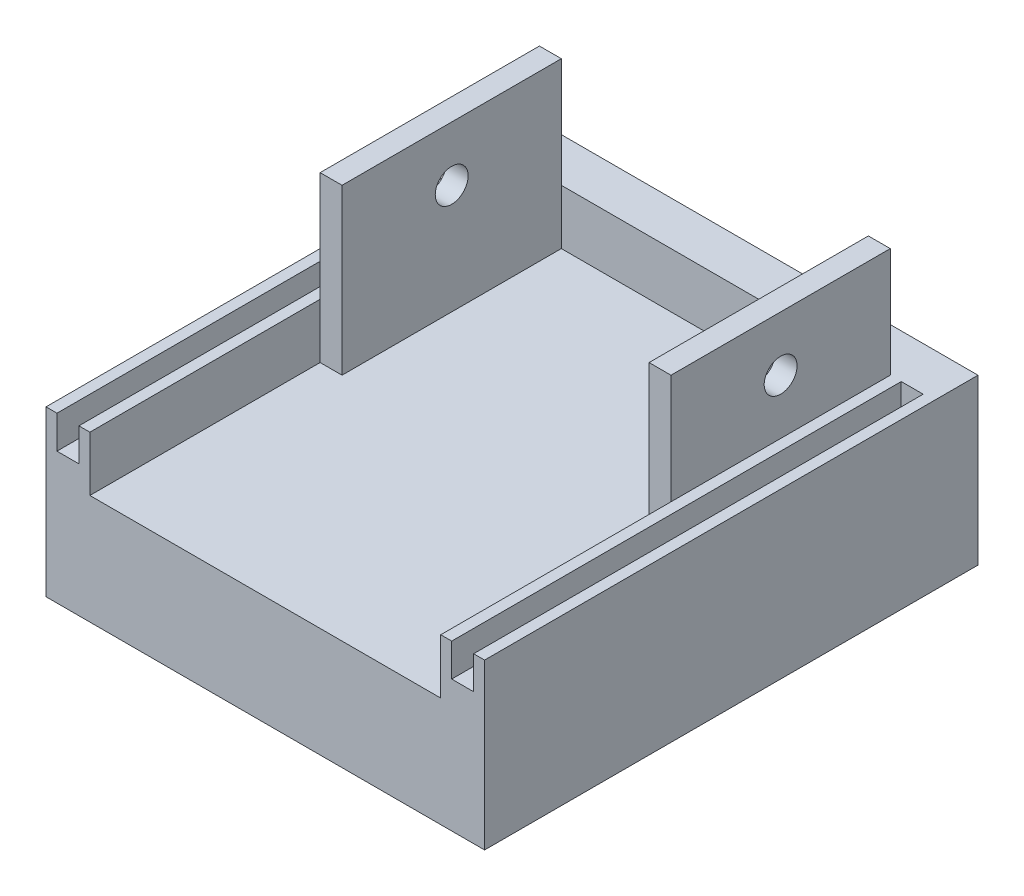
SolidWorks part; units mm, degrees
ref_plane "Front Plane" through (0, 0, 0) normal (0, 0, 1) x (1, 0, 0)
ref_plane "Top Plane" through (0, 0, 0) normal (0, 1, 0) x (1, 0, 0)
ref_plane "Right Plane" through (0, 0, 0) normal (1, 0, 0) x (0, 0, -1)
sketch "Sketch1" plane through (0, 0, 0) normal (0, 1, 0) x (1, 0, 0)
  line L1 (-20, -22.5) -> (20, -22.5)
  line L2 (-20, -22.5) -> (-20, 22.5)
  line L3 (-20, 22.5) -> (20, 22.5)
  line L4 (20, -22.5) -> (20, 22.5)
  line L5 (-20, -22.5) -> (20, 22.5) construction
  line L6 (-20, 22.5) -> (20, -22.5) construction
  point P0 (0, 0)
  dimension "D1" = 40
  dimension "D2" = 45
extrude "Boss-Extrude1" add sketch "Sketch1" along normal blind 10
sketch "Sketch2" plane through (0, 10, 0) normal (0, 1, 0) x (1, 0, 0)
  line L0 (20, -22.5) -> (20, 22.5) construction
  line L1 (-20, 22.5) -> (20, 22.5)
  line L2 (-20, 22.5) -> (-20, 18.5)
  line L3 (-20, 18.5) -> (20, 18.5)
  line L4 (20, 22.5) -> (20, 18.5)
  dimension "D1" = 4
extrude "Boss-Extrude2" add sketch "Sketch2" along normal blind 5
sketch "Sketch3" plane through (0, 10, 0) normal (0, 1, 0) x (1, 0, 0)
  line L0 (-20, 18.5) -> (20, 18.5) construction
  line L1 (-20, -22.5) -> (-16, -22.5)
  line L2 (-20, -22.5) -> (-20, 18.5)
  line L3 (-20, 18.5) -> (-16, 18.5)
  line L4 (-16, -22.5) -> (-16, 18.5)
  dimension "D1" = 4
extrude "Boss-Extrude3" add sketch "Sketch3" along normal blind 5
sketch "Sketch4" plane through (0, 15, 0) normal (0, 1, 0) x (1, 0, 0)
  line L0 (-16, 18.5) -> (-20, 18.5) construction
  line L1 (-20, 22.5) -> (-20, -22.5) construction
  line L2 (-18, 18.5) -> (-18, -22.5) construction
  line L3 (-20, -22.5) -> (-16, -22.5) construction
  line L5 (-19, -22.5) -> (-17, -22.5)
  line L6 (-19, -22.5) -> (-19, 18.5)
  line L7 (-19, 18.5) -> (-17, 18.5)
  line L8 (-17, -22.5) -> (-17, 18.5)
  dimension "D1" = 2
extrude "Cut-Extrude1" cut sketch "Sketch4" against normal blind 3
mirror "Mirror1" about plane through (0, 0, 0) normal (1, 0, 0) of "Cut-Extrude1", "Boss-Extrude3"
sketch "Sketch5" plane through (0, 10, 0) normal (0, 1, 0) x (1, 0, 0)
  line L1 (-16, 18.5) -> (-14, 18.5)
  line L2 (-16, 18.5) -> (-16, -1.5)
  line L3 (-16, -1.5) -> (-14, -1.5)
  line L4 (-14, 18.5) -> (-14, -1.5)
  dimension "D1" = 2
  dimension "D2" = 20
extrude "Boss-Extrude4" add sketch "Sketch5" along normal blind 15
mirror "Mirror2" about plane through (0, 0, 0) normal (1, 0, 0) of "Boss-Extrude4"
sketch "Sketch8" plane through (16, 0, 0) normal (1, 0, 0) x (0, 0, -1)
  line L0 (18.5, 25) -> (18.5, 15) construction
  line L1 (18.5, 25) -> (-1.5, 25) construction
  circle A0 centre (8.5, 20) radius 1.5
  dimension "D1" = 10
  dimension "D2" = 5
  dimension "D3" = 3
extrude "Cut-Extrude2" cut sketch "Sketch8" against normal through all both and the other way through all
